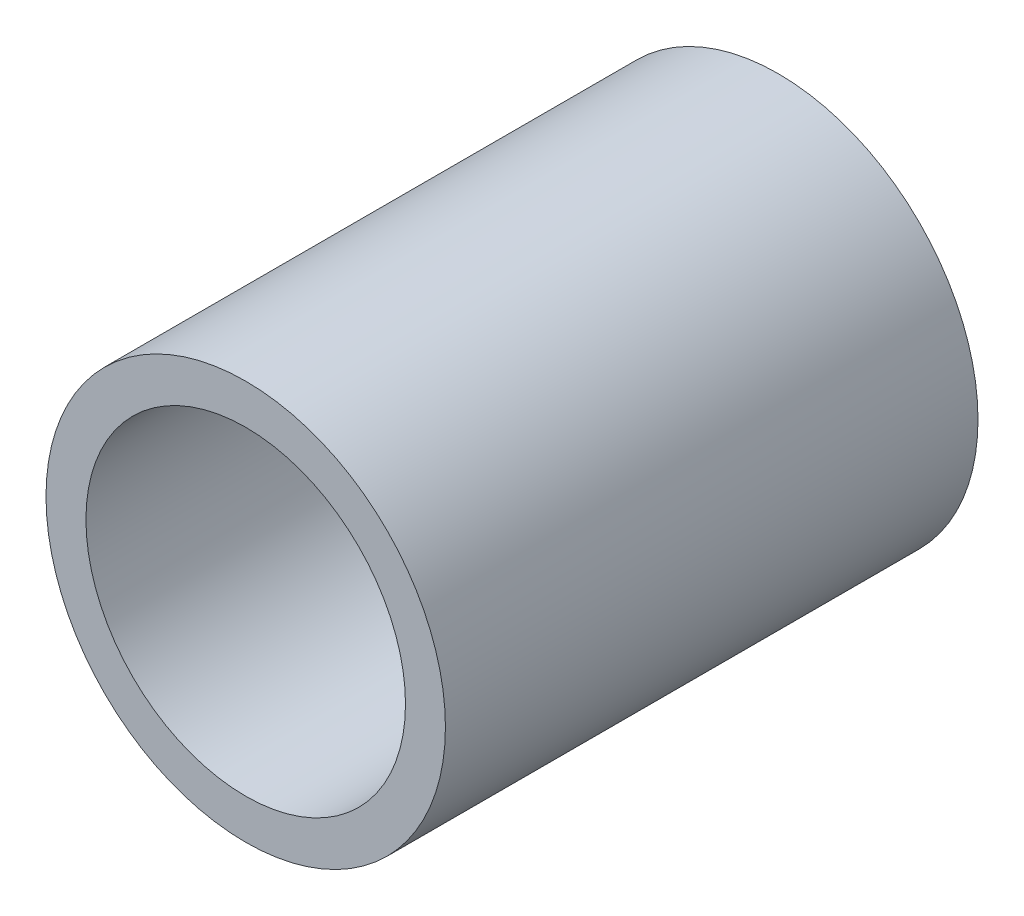
SolidWorks part; units mm, degrees
ref_plane "前视基准面" through (0, 0, 0) normal (0, 0, 1) x (1, 0, 0)
ref_plane "上视基准面" through (0, 0, 0) normal (0, 1, 0) x (1, 0, 0)
ref_plane "右视基准面" through (0, 0, 0) normal (1, 0, 0) x (0, 0, -1)
other "Configuration Table"
sketch "草图1" plane through (0, 0, 0) normal (0, 0, 1) x (1, 0, 0)
  circle A0 centre (0, 0) radius 7.5
  circle A1 centre (0, 0) radius 6
  dimension "D1" = 15
  dimension "D2" = 12
extrude "凸台-拉伸1" add sketch "草图1" along normal mid plane 20
